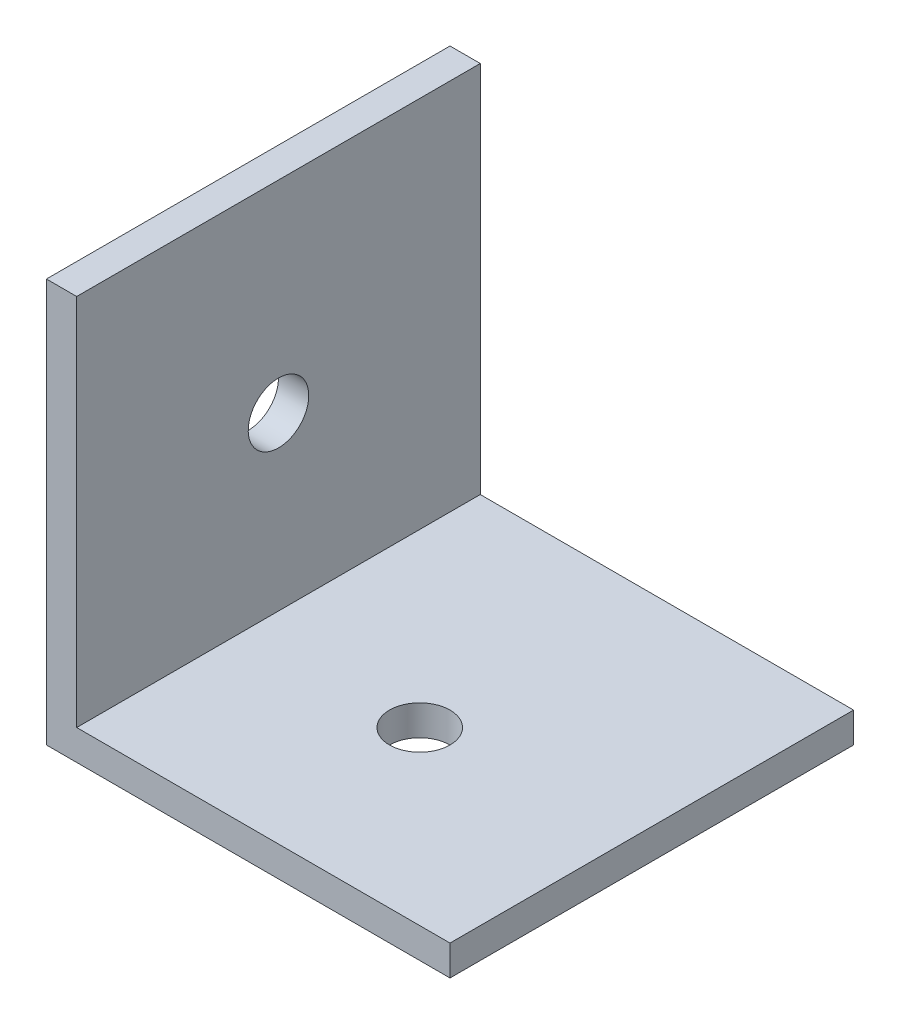
SolidWorks part; units mm, degrees
ref_plane "Plan de face" through (0, 0, 0) normal (0, 0, 1) x (1, 0, 0)
ref_plane "Plan de dessus" through (0, 0, 0) normal (0, 1, 0) x (1, 0, 0)
ref_plane "Plan de droite" through (0, 0, 0) normal (1, 0, 0) x (0, 0, -1)
sketch "Esquisse1" plane through (0, 0, 0) normal (0, 0, 1) x (1, 0, 0)
  line L0 (0, 0) -> (20, 0)
  line L1 (20, 0) -> (20, 1.5)
  line L2 (20, 1.5) -> (1.5, 1.5)
  line L3 (1.5, 1.5) -> (1.5, 20)
  line L4 (1.5, 20) -> (0, 20)
  line L5 (0, 20) -> (0, 0)
  dimension "D1" = 1.5
  dimension "D2" = 1.5
  dimension "D3" = 20
  dimension "D4" = 20
extrude "Extrusion1" add sketch "Esquisse1" along normal blind 20
sketch "Esquisse7" plane through (0, 1.5, 0) normal (0, 1, 0) x (-1, 0, 0)
  line L0 (-20, 20) -> (-20, 0) construction
  line L1 (-20, 20) -> (-1.5, 20) construction
  circle A0 centre (-10, 11.5) radius 1.5
  dimension "D2" = 10
  dimension "D3" = 8.5
extrude "Extrusion7" cut sketch "Esquisse7" against normal through all
sketch "Esquisse9" plane through (1.5, 0, 0) normal (1, 0, 0) x (0, 0, -1)
  line L0 (-20, 1.5) -> (-20, 20) construction
  line L1 (-20, 20) -> (0, 20) construction
  circle A0 centre (-10, 10) radius 1.5
  dimension "D1" = 10
  dimension "D3" = 10
extrude "Extrusion8" cut sketch "Esquisse9" against normal through all
